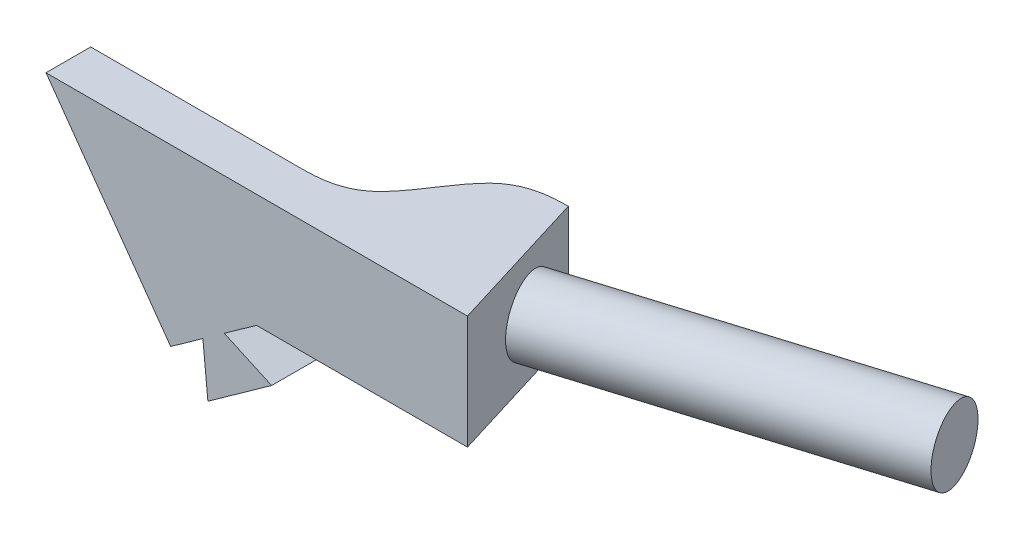
SolidWorks part; units mm, degrees
material "Custom Plastic"
ref_plane "X-Y Datum" through (0, 0, 0) normal (0, 0, 1) x (1, 0, 0)
ref_plane "X-Z Datum" through (0, 0, 0) normal (0, 1, 0) x (1, 0, 0)
ref_plane "Y-Z Datum" through (0, 0, 0) normal (1, 0, 0) x (0, 0, -1)
sketch "Sketch1" plane through (0, 0, 0) normal (0, 0, 1) x (1, 0, 0)
  line L1 (-38.1, -12.7) -> (38.1, -12.7)
  line L2 (-38.1, -12.7) -> (-38.1, 12.7)
  line L3 (-38.1, 12.7) -> (38.1, 12.7)
  line L4 (38.1, -12.7) -> (38.1, 12.7)
  line L5 (-38.1, -12.7) -> (38.1, 12.7) construction
  line L6 (-38.1, 12.7) -> (38.1, -12.7) construction
  point P0 (0, 0)
  dimension "D1" = 25.4
  dimension "D2" = 76.2
extrude "Boss-Extrude1" add sketch "Sketch1" along normal blind 12.7 and the other way blind 19.8782
sketch "Sketch2" plane through (0, -12.7, 0) normal (0, -1, 0) x (1, 0, 0)
  line L0 (28.0956, -19.8782) -> (38.1, 12.7)
  line L1 (-38.1, -19.8782) -> (38.1, -19.8782) construction
  line L2 (28.0956, -19.8782) -> (38.1, -19.8782)
  line L3 (38.1, -19.8782) -> (38.1, 12.7)
  line L4 (33.0978, -3.5891) -> (86.5661, -20.0085)
  line L5 (-38.1, 12.7) -> (38.1, 12.7) construction
  line L6 (-9.1056, 2.7) -> (-38.1, 2.7)
  line L7 (-38.1, -19.8782) -> (-38.1, 12.7) construction
  line L8 (30.3, -19.8782) -> (13.797, -19.8782)
  line L9 (-38.1, -19.8782) -> (-38.1, 2.7)
  line L10 (28.0956, -19.8782) -> (-38.1, -19.8782)
  spline S0 degree 3 poles (28.0956, -19.8782) (23.2625, -19.8782) (13.7597, -18.3883) (5.193, 1.2101) (-4.1851, 2.7) (-9.1056, 2.7) knots 0 0 0 0 0.311689 0.688311 1 1 1 1
  point P7 (33.0978, -3.5891)
  line M5 (38.1, -19.8782) -> (38.1, 12.7)
  line M8 (-38.1, -19.8782) -> (38.1, -19.8782)
  dimension "D1" = 17.071
  dimension "D2" = 28.9944
  dimension "D3" = 10
  dimension "D4" = 3.81
  dimension "D5" = 3.81
  dimension "D6" = 12.7
  dimension "D7" = 12.7
extrude "Cut-Extrude1" cut sketch "Sketch2" against normal through all contours L4 L0 M8 M5 | L0 L4 L3 | L10 L9 L6 S0
sketch "Sketch4" plane through (31.2528, 0, -9.5973) normal (0.9559, 0, -0.2936) x (-0.2936, 0, -0.9559)
  line L1 (-23.325, -12.7) -> (-23.325, 12.7) construction
  circle A0 centre (-2.5307, 0) radius 7.9375
  dimension "D1" = 15.875
  dimension "D2" = 20.7943
extrude "Boss-Extrude2" add sketch "Sketch4" along normal blind 76.2
sketch "Sketch5" plane through (0, 0, 2.7) normal (0, 0, -1) x (-1, 0, 0)
  line L0 (38.1, -12.7) -> (56.2176, 12.7)
  line L1 (56.2176, 12.7) -> (38.1, 12.7)
  line L2 (0, 0) -> (72.4016, 0) construction
  line L3 (72.4016, 0) -> (-9.0548, 58.1023) construction
  line L4 (38.1, 12.7) -> (38.1, -12.7)
  line L5 (9.1056, -12.7) -> (28.3226, -26.4074)
  line L6 (28.3226, -26.4074) -> (38.1, -12.7)
  line L7 (38.1, -12.7) -> (9.1056, -12.7)
  line L8 (16.3197, -17.8458) -> (5.7244, -22.6744)
  line L9 (5.7244, -22.6744) -> (19.9925, -32.8518)
  line L10 (19.9925, -32.8518) -> (21.1086, -21.2616)
  line L11 (12.8585, -27.7631) -> (18.7141, -19.5537) construction
  line L12 (16.3197, -17.8458) -> (21.1086, -21.2616)
  line M4 (9.1056, -12.7) -> (38.1, -12.7)
  line M5 (38.1, -12.7) -> (38.1, 12.7)
  dimension "D1" = 35.5
  dimension "D2" = 60
  dimension "D3" = 60
  dimension "D4" = 17.526
  dimension "D5" = 10.0838
extrude "Boss-Extrude3" add sketch "Sketch5" against normal up to surface (10 mm away) contours L5 L6 M4 | L0 L1 M5 | L12 L10 L9 L8 up to face at (0, 0, 12.7)
sketch "Sketch6" [suppressed] plane through (0, 0, 2.7) normal (0, 0, -1) x (-1, 0, 0)
  line L0 (0, 0) -> (115.4941, 0) construction
  line L1 (115.4941, 0) -> (-60.7221, -126.1584) construction
  line L2 (38.1, 12.7) -> (56.2846, -12.7)
  line L3 (56.2846, -12.7) -> (38.1, -12.7)
  line L4 (38.1, -12.7) -> (38.1, 12.7)
  line L5 (38.1, 12.7) -> (28.2748, 26.4237)
  line L6 (28.2748, 26.4237) -> (9.1056, 12.7)
  line L7 (9.1056, 12.7) -> (38.1, 12.7) construction
  line L8 (9.1056, 12.7) -> (38.1, 12.7)
  line L9 (16.2988, 17.8498) -> (5.695, 22.6599)
  line L10 (5.695, 22.6599) -> (19.9454, 32.8622)
  line L11 (19.9454, 32.8622) -> (21.0816, 21.274)
  line L12 (12.8202, 27.761) -> (18.6902, 19.5619) construction
  line L13 (16.2988, 17.8498) -> (21.0816, 21.274)
  line M5 (38.1, -12.7) -> (38.1, 12.7)
  line M6 (38.1, 12.7) -> (9.1056, 12.7)
  dimension "D1" = 35.7
  dimension "D2" = 60
  dimension "D3" = 60
  dimension "D4" = 10.0838
  dimension "D5" = 17.526
extrude "Boss-Extrude4" [suppressed] add sketch "Sketch6" against normal up to surface (10 mm away) contours L3 L2 M5 | L5 L6 M6 | L13 L11 L10 L9
